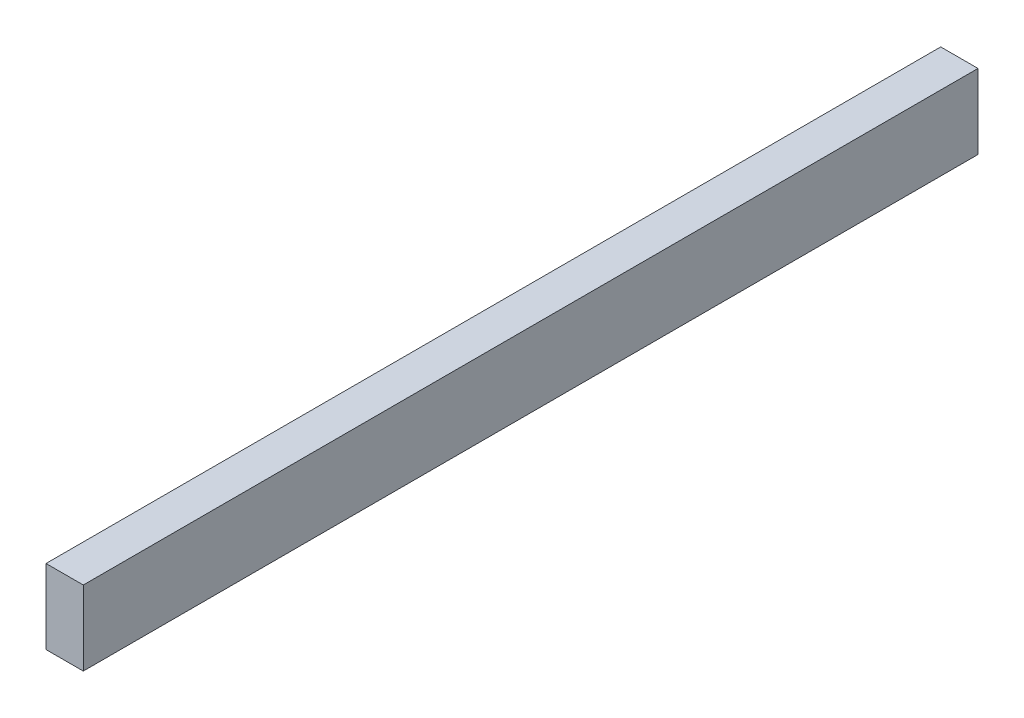
SolidWorks part; units mm, degrees
ref_plane "Front Plane" through (0, 0, 0) normal (0, 0, 1) x (1, 0, 0)
ref_plane "Top Plane" through (0, 0, 0) normal (0, 1, 0) x (1, 0, 0)
ref_plane "Right Plane" through (0, 0, 0) normal (1, 0, 0) x (0, 0, -1)
sketch "Sketch1" plane through (0, 0, 0) normal (0, 0, 1) x (1, 0, 0)
  line L1 (-25.4, -50.8) -> (25.4, -50.8)
  line L2 (-25.4, -50.8) -> (-25.4, 50.8)
  line L3 (-25.4, 50.8) -> (25.4, 50.8)
  line L4 (25.4, -50.8) -> (25.4, 50.8)
  line L5 (-25.4, -50.8) -> (25.4, 50.8) construction
  line L6 (-25.4, 50.8) -> (25.4, -50.8) construction
  point P0 (0, 0)
  dimension "D1" = 50.8
  dimension "D2" = 101.6
extrude "Boss-Extrude1" add sketch "Sketch1" along normal blind 1219.2
